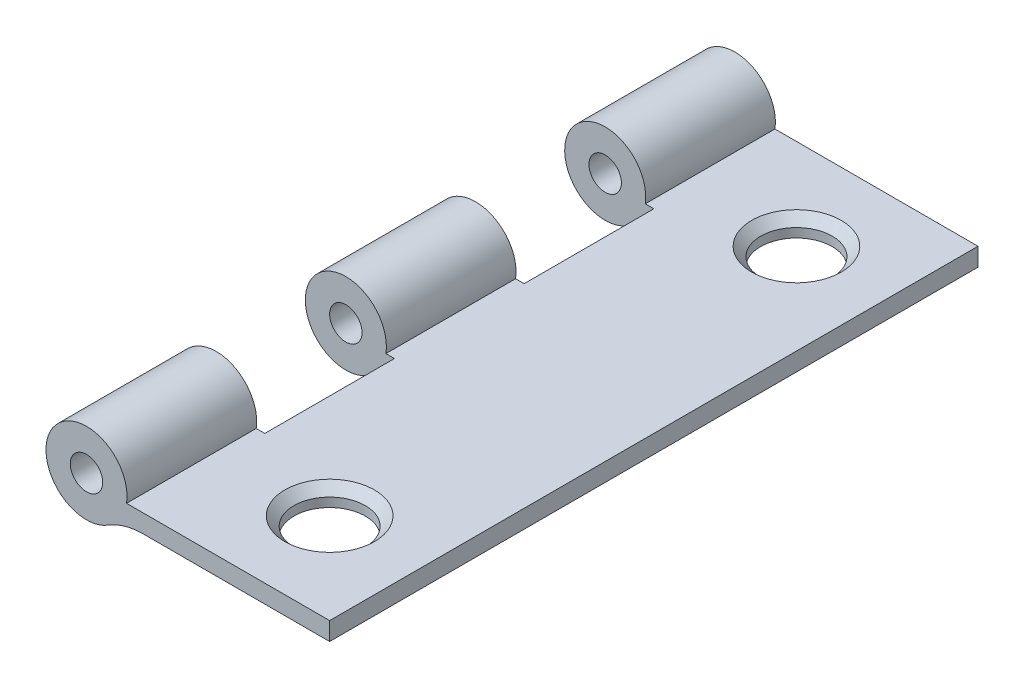
SolidWorks part; units mm, degrees
ref_plane "Front Plane" through (0, 0, 0) normal (0, 0, 1) x (1, 0, 0)
ref_plane "Top Plane" through (0, 0, 0) normal (0, 1, 0) x (1, 0, 0)
ref_plane "Right Plane" through (0, 0, 0) normal (1, 0, 0) x (0, 0, -1)
sketch "Sketch4" plane through (0, 0, 0) normal (0, 0, 1) x (1, 0, 0)
  line L0 (19.05, -0.4826) -> (3.1381, -0.4826)
  line L1 (19.05, -1.905) -> (2.54, -1.905)
  line L2 (19.05, -1.905) -> (19.05, -0.4826)
  circle A0 centre (0, 0) radius 3.175
  dimension "D1" = 6.35
  dimension "D2" = 15.9119
  dimension "D3" = 1.27
  dimension "D4" = 1.4224
extrude "Boss-Extrude2" add sketch "Sketch4" along normal mid plane 50.8 contours A0 | A0 L1 L2 L0
fillet "Fillet1" radius 5.08 1 edges at (2.54, -1.905, 0)
hole_wizard "M5 Clearance Hole1" positions "Sketch6" profile "Sketch7" hole size "M5" standard "ANSI Metric" end condition up to next
sketch "Sketch6" plane through (0, -0.4826, 0) normal (0, 1, 0) x (1, 0, 0)
  line L0 (19.05, -25.4) -> (19.05, 25.4) construction
  point P0 (11.938, 18.288)
  point P2 (11.938, -18.288)
  dimension "D1" = 18.288
  dimension "D2" = 18.288
  dimension "D3" = 7.112
sketch "Sketch7" plane through (11.938, -0.4826, -18.288) normal (1, 0, 0) x (0, 0, 1)
  line L0 (0, 0) -> (0, 1.4224)
  line L1 (0, 1.4224) -> (2.8, 1.4224)
  line L2 (2.8, 1.4224) -> (2.8, 0)
  line L5 (2.8, 0) -> (0, 0)
  line L11 (0, -6.35) -> (0, 107.95) construction
  dimension "Thru Hole Dia." = 5.6
  dimension "Thru Hole Depth" = 1.4224
sketch "Sketch9" plane through (0, 0, 0) normal (0, 1, 0) x (1, 0, 0)
  line L0 (-3.175, 25.4) -> (-3.175, -25.4)
  line L2 (3.81, 25.4) -> (3.81, -25.4)
  line L3 (19.05, 25.4) -> (3.1381, 25.4) construction
  line L4 (19.05, -25.4) -> (3.1381, -25.4) construction
  line L5 (3.175, -25.4) -> (3.175, 25.4) construction
  line L7 (-3.175, 15.24) -> (3.81, 15.24)
  line L8 (-3.175, 5.08) -> (3.81, 5.08)
  line L9 (-3.175, -5.08) -> (3.81, -5.08)
  line L10 (-3.175, -15.24) -> (3.81, -15.24)
  point P4 (-3.175, 15.24)
  point P5 (-3.175, 5.08)
  point P6 (-3.175, -5.08)
  point P7 (-3.175, -15.24)
  dimension "D1" = 0.635
extrude "Cut-Extrude1" cut sketch "Sketch9" against normal through all both and the other way through all contours L0 L8 L2 L7 | L0 L10 L2 L9
sketch "Sketch10" plane through (0, 0, 25.4) normal (0, 0, 1) x (1, 0, 0)
  circle A0 centre (0, 0) radius 1.27
  dimension "D1" = 2.54
extrude "Cut-Extrude2" cut sketch "Sketch10" against normal through all
chamfer "Chamfer1" distance 0.7112 angle 45 2 edges at (11.938, -0.4826, -15.488) (11.938, -0.4826, 21.088)
equation "\"D2@Sketch6\"=\"D1@Sketch6\""
